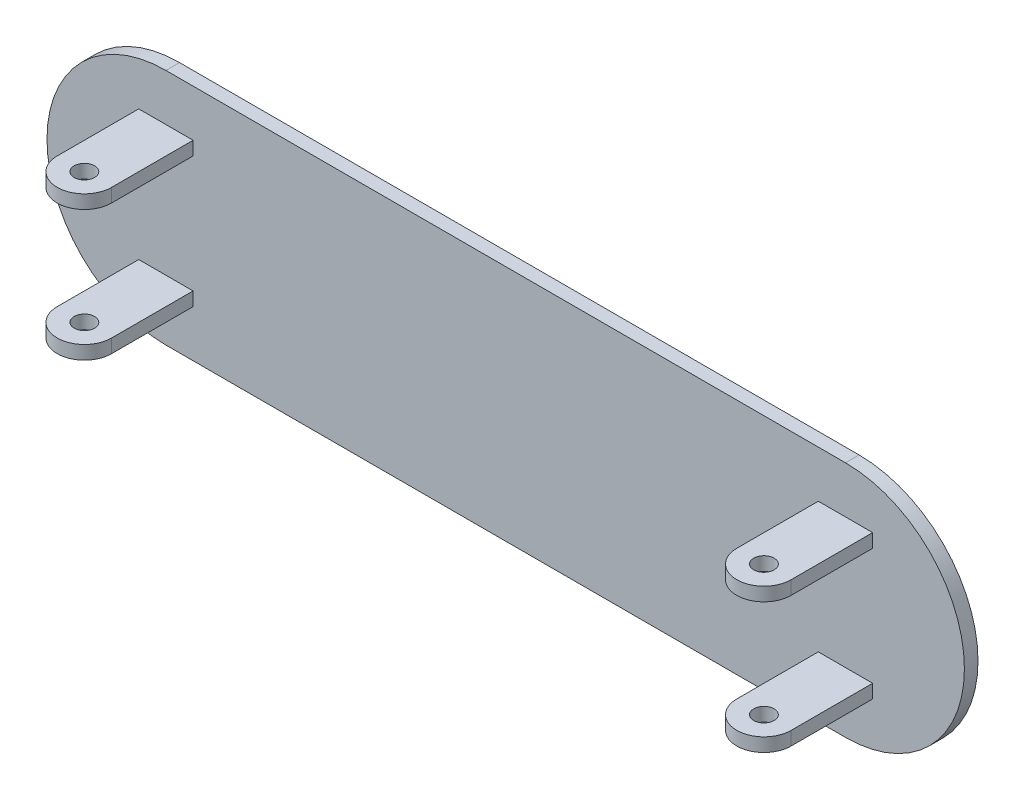
SolidWorks part; units mm, degrees
ref_plane "Front Plane" through (0, 0, 0) normal (0, 0, 1) x (1, 0, 0)
ref_plane "Top Plane" through (0, 0, 0) normal (0, 1, 0) x (1, 0, 0)
ref_plane "Right Plane" through (0, 0, 0) normal (1, 0, 0) x (0, 0, -1)
sketch "Sketch1" plane through (0, 0, 0) normal (0, 0, 1) x (1, 0, 0)
  line L0 (-50, 0) -> (50, 0) construction
  line L1 (-50, 17.5) -> (50, 17.5)
  line L2 (-50, -17.5) -> (50, -17.5)
  arc A0 (-50, 17.5) -> (-50, -17.5) centre (-50, 0) ccw
  arc A1 (50, -17.5) -> (50, 17.5) centre (50, 0) ccw
  point P3 (0, 0)
  dimension "D2" = 100
  dimension "D1" = 35
extrude "Boss-Extrude3" add sketch "Sketch1" along normal mid plane 2
sketch "Sketch2" plane through (0, 0, 1) normal (0, 0, 1) x (1, 0, 0)
  line L1 (-54, 8.6) -> (-46, 8.6)
  line L2 (-54, 8.6) -> (-54, 10.6)
  line L3 (-54, 10.6) -> (-46, 10.6)
  line L4 (-46, 8.6) -> (-46, 10.6)
  line L5 (-54, 8.6) -> (-46, 10.6) construction
  line L6 (-54, 10.6) -> (-46, 8.6) construction
  point P0 (-50, 9.6)
  dimension "D1" = 10.6
  dimension "D2" = 8
  dimension "D3" = 2
  dimension "D4" = 50
extrude "Boss-Extrude4" add sketch "Sketch2" along normal blind 20
sketch "Sketch5" plane through (0, 8.6, 0) normal (0, -1, 0) x (1, 0, 0)
  line L0 (-46, 21) -> (-46, 1) construction
  line L1 (-54, 21) -> (-54, 1) construction
  line L2 (-54, 1) -> (-46, 1) construction
  line L3 (-54, 13) -> (-54, 21)
  line L4 (-54, 21) -> (-46, 21)
  line L5 (-46, 21) -> (-46, 13)
  arc A0 (-46, 13) -> (-54, 13) centre (-50, 13) ccw
  circle A1 centre (-50, 13) radius 1.5
  dimension "D2" = 3
  dimension "D1" = 12
extrude "Cut-Extrude1" cut sketch "Sketch5" against normal blind 2
mirror "Mirror1" about plane through (0, 0, 0) normal (0, 1, 0) of "Cut-Extrude1", "Boss-Extrude4"
mirror "Mirror2" about plane through (0, 0, 0) normal (1, 0, 0) of "Mirror1", "Boss-Extrude4", "Cut-Extrude1"
